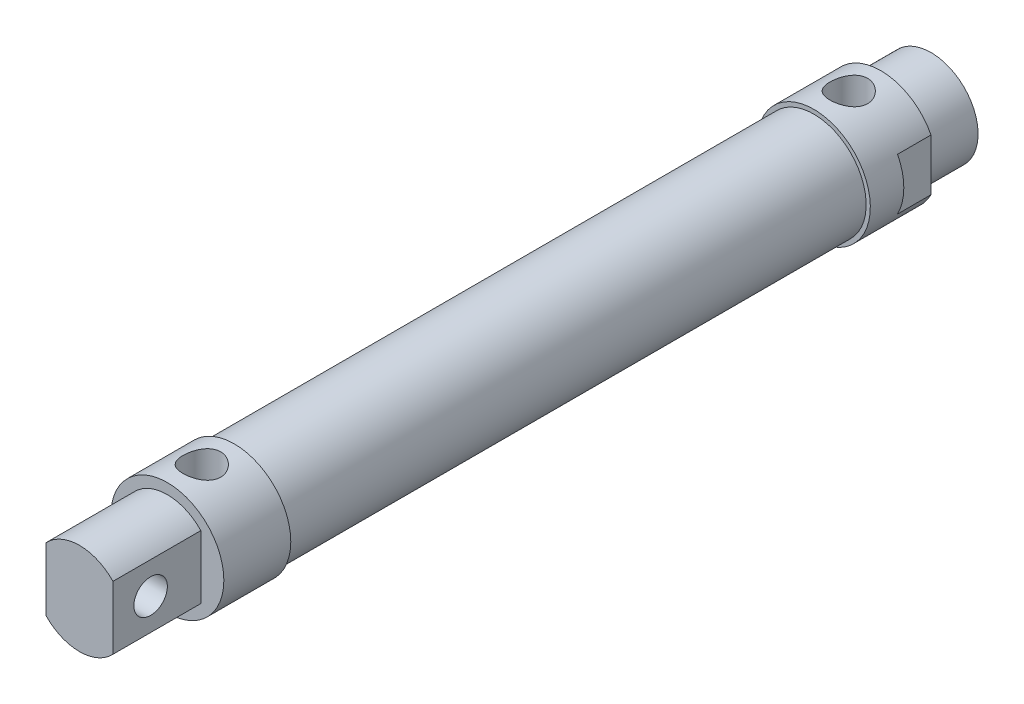
SolidWorks part; units mm, degrees
ref_plane "Front Plane" through (0, 0, 0) normal (0, 0, 1) x (1, 0, 0)
ref_plane "Top Plane" through (0, 0, 0) normal (0, 1, 0) x (1, 0, 0)
ref_plane "Right Plane" through (0, 0, 0) normal (1, 0, 0) x (0, 0, -1)
sketch "Sketch1" plane through (0, 0, 0) normal (0, 0, 1) x (1, 0, 0)
  circle A0 centre (0, 0) radius 12.5
  dimension "D1" = 25
extrude "Boss-Extrude1" add sketch "Sketch1" along normal blind 138.5
sketch "Sketch2" plane through (0, 0, 138.5) normal (0, 0, 1) x (1, 0, 0)
  circle A0 centre (0, 0) radius 13.5
  dimension "D1" = 27
extrude "Boss-Extrude2" add sketch "Sketch2" along normal blind 37
sketch "Sketch3" plane through (0, 0, 0) normal (0, 0, -1) x (-1, 0, 0)
  circle A0 centre (0, 0) radius 13.5
  dimension "D1" = 27
extrude "Boss-Extrude3" add sketch "Sketch3" along normal blind 28
sketch "Sketch4" plane through (0, 0, 175.5) normal (0, 0, 1) x (1, 0, 0)
  line L0 (-8, 10.8743) -> (-8, -10.8743)
  line L1 (8, 10.8743) -> (8, -10.8743)
  circle A0 centre (0, 0) radius 13.5 construction
  arc A1 (-8, 10.8743) -> (-8, -10.8743) centre (0, 0) ccw
  arc A2 (8, -10.8743) -> (8, 10.8743) centre (0, 0) ccw
  dimension "D1" = 8
  dimension "D2" = 8
extrude "Cut-Extrude1" cut sketch "Sketch4" against normal blind 21
sketch "Sketch5" plane through (-8, 0, 0) normal (-1, 0, 0) x (0, 0, 1)
  line L0 (175.5, -10.8743) -> (175.5, 10.8743) construction
  circle A0 centre (166.5, 0) radius 4
  dimension "D1" = 8
  dimension "D2" = 9
extrude "Cut-Extrude2" cut sketch "Sketch5" against normal through all
sketch "Sketch6" plane through (0, 0, 175.5) normal (0, 0, 1) x (1, 0, 0)
  line L0 (8, 10.8743) -> (8, -10.8743) construction
  line L1 (-8, -10.8743) -> (-8, 10.8743) construction
  line L2 (8, 10.8743) -> (8, 7.5498)
  line L3 (-8, -10.8743) -> (-8, -7.5498)
  line L4 (8, -7.5498) -> (8, -10.8743)
  line L5 (-8, 7.5498) -> (-8, 10.8743)
  arc A0 (8, 7.5498) -> (-8, 7.5498) centre (0, 0) ccw
  arc A1 (-8, -10.8743) -> (8, -10.8743) centre (0, 0) ccw construction
  arc A2 (8, 10.8743) -> (-8, 10.8743) centre (0, 0) ccw construction
  arc A3 (-8, -10.8743) -> (8, -10.8743) centre (0, 0) ccw
  arc A4 (8, 10.8743) -> (-8, 10.8743) centre (0, 0) ccw
  arc A5 (-8, -7.5498) -> (8, -7.5498) centre (0, 0) ccw
  dimension "D1" = 22
extrude "Cut-Extrude4" cut sketch "Sketch6" against normal blind 21
sketch "Sketch7" plane through (0, 0, -28) normal (0, 0, -1) x (-1, 0, 0)
  line L2 (-12, 6.1847) -> (-12, -6.1847)
  line L3 (12, 6.1847) -> (12, -6.1847)
  circle A0 centre (0, 0) radius 13.5 construction
  arc A1 (-12, 6.1847) -> (-12, -6.1847) centre (0, 0) ccw
  arc A2 (12, -6.1847) -> (12, 6.1847) centre (0, 0) ccw
  dimension "D1" = 12
  dimension "D2" = 12
extrude "Cut-Extrude5" cut sketch "Sketch7" against normal blind 20
sketch "Sketch8" plane through (0, 0, -28) normal (0, 0, -1) x (-1, 0, 0)
  circle A0 centre (0, 0) radius 11.25
  dimension "D1" = 22.5
extrude "Cut-Extrude6" cut sketch "Sketch8" against normal blind 12 flip side to cut
ref_plane "Plane1" through (0, 15, 0) normal (0, 1, 0) x (-1, 0, 0)
sketch "Sketch10" plane through (0, 15, 0) normal (0, 1, 0) x (-1, 0, 0)
  circle A0 centre (0, 146.2668) radius 4.5
  circle A1 centre (0, -8.3321) radius 4.5
  dimension "D1" = 9
  dimension "D2" = 9
extrude "Cut-Extrude7" cut sketch "Sketch10" against normal blind 12
sketch "Sketch11" plane through (0, 0, -28) normal (0, 0, -1) x (-1, 0, 0)
  circle A0 centre (0, 0) radius 4
  dimension "D1" = 8
extrude "Cut-Extrude8" cut sketch "Sketch11" against normal blind 12
sketch "Sketch13"
sketch_block_instance "Block1-1"
sketch_block "Block1" parameters "D1"=130, "D2"=20
